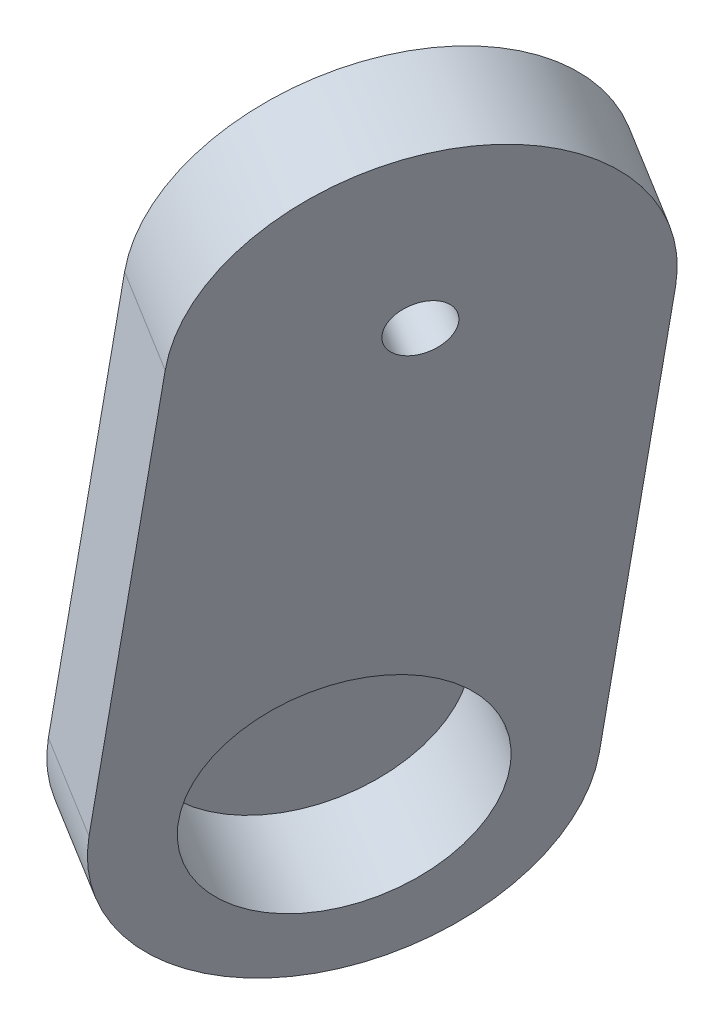
SolidWorks part; units mm, degrees
material "ABS"
ref_plane "Спереди" through (0, 0, 0) normal (0, 0, 1) x (1, 0, 0)
ref_plane "Сверху" through (0, 0, 0) normal (0, 1, 0) x (1, 0, 0)
ref_plane "Справа" through (0, 0, 0) normal (1, 0, 0) x (0, 0, -1)
sketch "Эскиз1" plane through (-480.8038, 134.6521, -243.8867) normal (0.8652, -0.2423, 0.4389) x (0.4445, -0.0342, -0.8951)
  line L0 (-678.1229, -142.8376) -> (-678.1229, -168.8376) construction
  line L1 (-688.1229, -142.8376) -> (-688.1229, -168.8376)
  line L2 (-668.1229, -142.8376) -> (-668.1229, -168.8376)
  circle A0 centre (-678.1229, -142.8376) radius 1.5
  circle A1 centre (-678.1229, -142.8376) radius 10 construction
  circle A2 centre (-678.1229, -168.8376) radius 6.5
  circle A3 centre (-678.1229, -168.8376) radius 10 construction
  arc A4 (-668.1229, -142.8376) -> (-688.1229, -142.8376) centre (-678.1229, -142.8376) ccw
  arc A5 (-688.1229, -168.8376) -> (-668.1229, -168.8376) centre (-678.1229, -168.8376) ccw
  dimension "D1" = 3
  dimension "D2" = 20
  dimension "D3" = 26
  dimension "D4" = 13
extrude "Бобышка-Вытянуть1" add sketch "Эскиз1" along normal blind 5
sketch "Эскиз3" plane through (-480.8038, 134.6521, -243.8867) normal (-0.8652, 0.2423, -0.4389) x (0.1058, 0.944, 0.3126)
  circle A0 centre (16.949, -698.6198) radius 8
  dimension "D1" = 16
extrude "Бобышка-Вытянуть2" add sketch "Эскиз3" along normal blind 2
